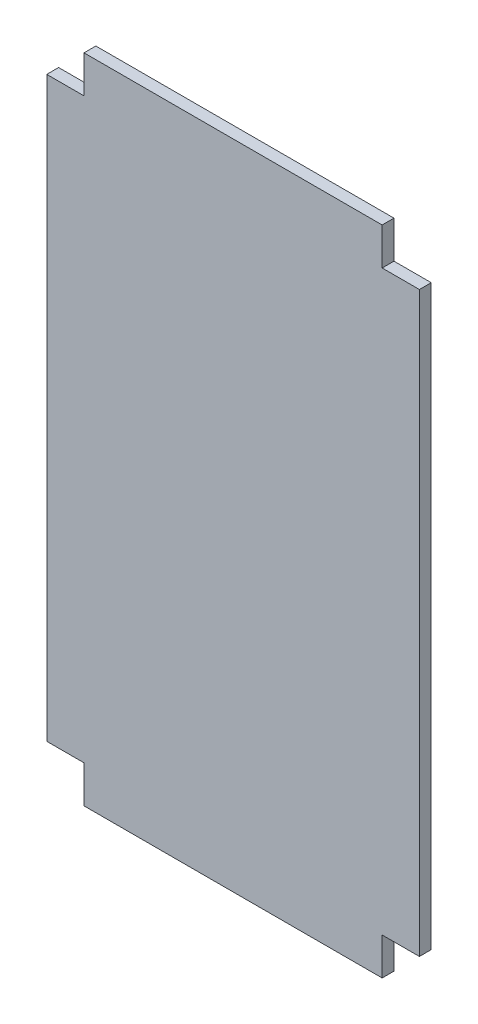
SolidWorks part; units mm, degrees
ref_plane "Front Plane" through (0, 0, 0) normal (0, 0, 1) x (1, 0, 0)
ref_plane "Top Plane" through (0, 0, 0) normal (0, 1, 0) x (1, 0, 0)
ref_plane "Right Plane" through (0, 0, 0) normal (1, 0, 0) x (0, 0, -1)
sketch "Sketch1" plane through (0, 0, 0) normal (0, 0, 1) x (1, 0, 0)
  line L1 (-155, -195) -> (5, -195)
  line L2 (-175, -175) -> (-175, 135)
  line L5 (-175, -175) -> (-155, -175)
  line L6 (-175, -175) -> (-175, 135)
  line L12 (-155, -175) -> (-155, -195)
  line L15 (-175, 135) -> (-155, 135)
  line L16 (-155, 155) -> (-155, 135)
  line L17 (-155, 135) -> (-155, 155)
  line L18 (-155, 155) -> (5, 155)
  line L20 (5, 135) -> (5, 155)
  line L21 (-175, 135) -> (-155, 135)
  line L22 (-155, 135) -> (-155, 155)
  line L24 (-155, -195) -> (5, -195)
  line L25 (5, -195) -> (5, -175)
  line L26 (5, 155) -> (5, 135)
  line L27 (5, 135) -> (25, 135)
  line L28 (25, 135) -> (25, -175)
  line L30 (25, -175) -> (5, -175)
  point P0 (0, 0)
extrude "Boss-Extrude1" add sketch "Sketch1" along normal blind 6.35
